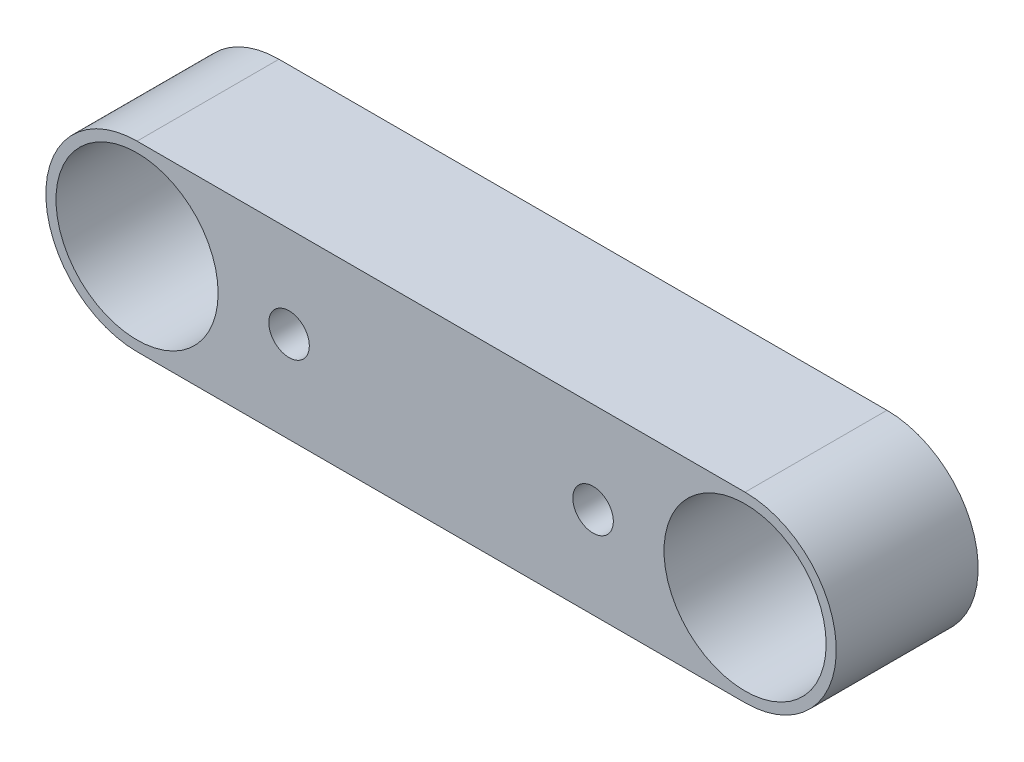
SolidWorks part; units mm, degrees
material "Nylon 101"
ref_plane "Front" through (0, 0, 0) normal (0, 0, 1) x (1, 0, 0)
ref_plane "Top" through (0, 0, 0) normal (0, 1, 0) x (1, 0, 0)
ref_plane "Right" through (0, 0, 0) normal (1, 0, 0) x (0, 0, -1)
sketch "Sketch1" plane through (0, 0, 0) normal (0, 0, 1) x (1, 0, 0)
  line L0 (30, 0) -> (-30, 0) construction
  line L3 (0, 0) -> (0, 5.9547) construction
  line L4 (-30, 0) -> (30, 0) construction
  line L5 (-30, 9) -> (30, 9)
  line L6 (-30, -9) -> (30, -9)
  circle A2 centre (-15, 0) radius 2
  circle A3 centre (15, 0) radius 2
  arc A4 (-30, 9) -> (-30, -9) centre (-30, 0) ccw
  arc A5 (30, -9) -> (30, 9) centre (30, 0) ccw
  circle A6 centre (-30, 0) radius 8
  circle A7 centre (30, 0) radius 8
  point P4 (0, 0)
  point P6 (0, 0)
  dimension "D2" = 4
  dimension "D4" = 16
  dimension "D5" = 9
  dimension "D1" = 30
  dimension "D3" = 60
extrude "Boss-Extrude1" add sketch "Sketch1" along normal mid plane 14
